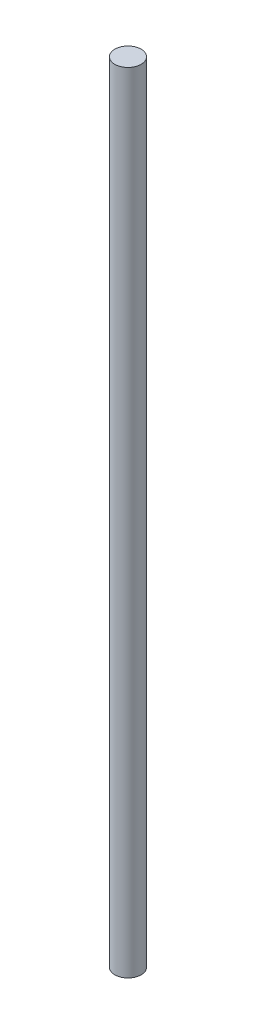
SolidWorks part; units mm, degrees
material "0.6010 (EN-GJL-100)"
ref_plane "Ön Düzlem" through (0, 0, 0) normal (0, 0, 1) x (1, 0, 0)
ref_plane "Üst Düzlem" through (0, 0, 0) normal (0, 1, 0) x (1, 0, 0)
ref_plane "Sağ Düzlem" through (0, 0, 0) normal (1, 0, 0) x (0, 0, -1)
sketch "Sketch7" plane through (6.7871, 0, -8.5398) normal (0, 1, 0) x (1, 0, 0)
  circle A0 centre (-57.4695, -38.3925) radius 20
  dimension "D1" = 40
extrude "Boss-Extrude6" add sketch "Sketch7" along normal blind 1200
